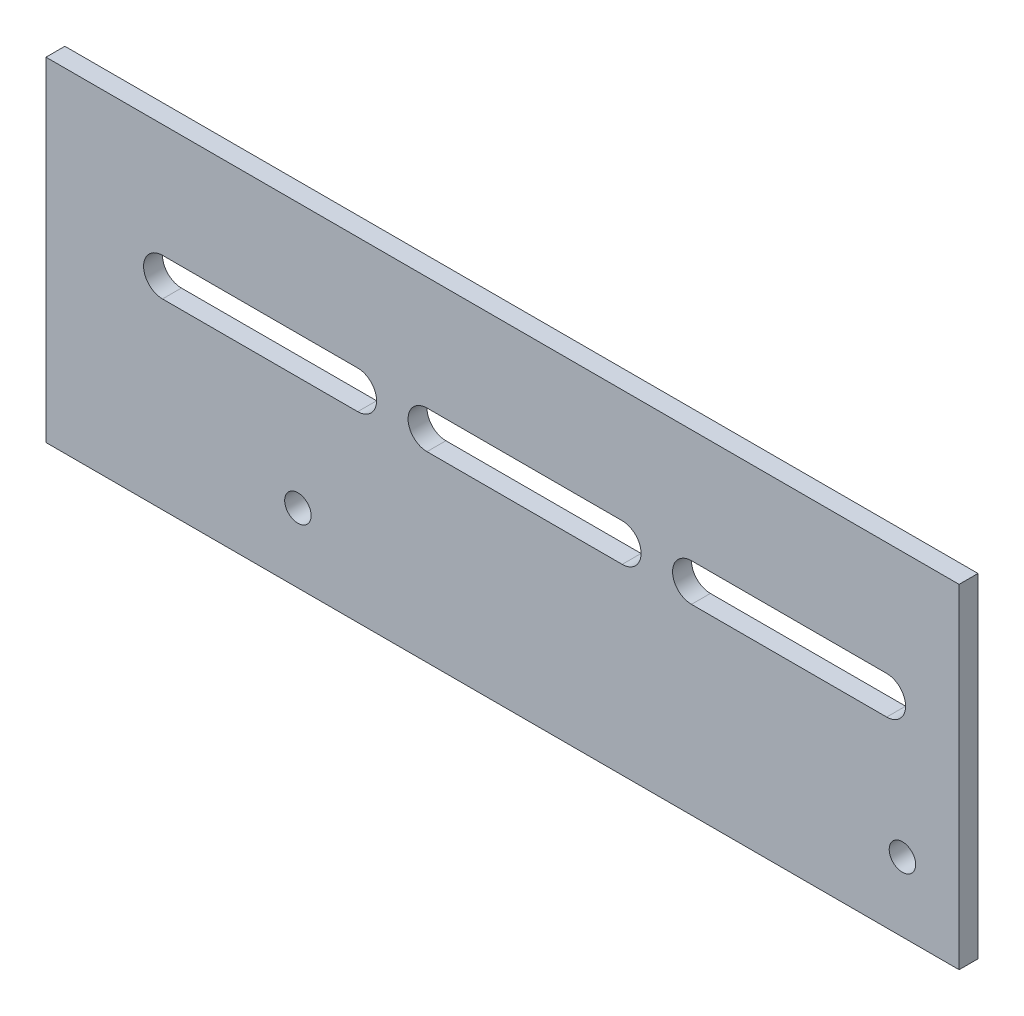
SolidWorks part; units mm, degrees
ref_plane "Front Plane" through (0, 0, 0) normal (0, 0, 1) x (1, 0, 0)
ref_plane "Top Plane" through (0, 0, 0) normal (0, 1, 0) x (1, 0, 0)
ref_plane "Right Plane" through (0, 0, 0) normal (1, 0, 0) x (0, 0, -1)
sketch "Lid riser with vents profile" plane through (0, 0, 0) normal (0, 0, 1) x (1, 0, 0)
  line L0 (-91, 50) -> (54, 50)
  line L1 (54, 50) -> (54, 103)
  line L2 (54, 103) -> (-91, 103)
  line L3 (-91, 103) -> (-91, 50)
  line L4 (-72.5, 79) -> (-41.5, 79)
  line L5 (-41.5, 85) -> (-72.5, 85)
  line L6 (-30.5, 79) -> (0.5, 79)
  line L7 (0.5, 85) -> (-30.5, 85)
  line L8 (11.5, 79) -> (42.5, 79)
  line L9 (42.5, 85) -> (11.5, 85)
  circle A0 centre (-51, 61) radius 2.1
  circle A1 centre (45, 61) radius 2.1
  arc A2 (-41.5, 79) -> (-41.5, 85) centre (-41.5, 82) ccw
  arc A3 (-72.5, 85) -> (-72.5, 79) centre (-72.5, 82) ccw
  arc A4 (0.5, 79) -> (0.5, 85) centre (0.5, 82) ccw
  arc A5 (-30.5, 85) -> (-30.5, 79) centre (-30.5, 82) ccw
  arc A6 (42.5, 79) -> (42.5, 85) centre (42.5, 82) ccw
  arc A7 (11.5, 85) -> (11.5, 79) centre (11.5, 82) ccw
extrude "Lid riser with vents" add sketch "Lid riser with vents profile" along normal blind 3
